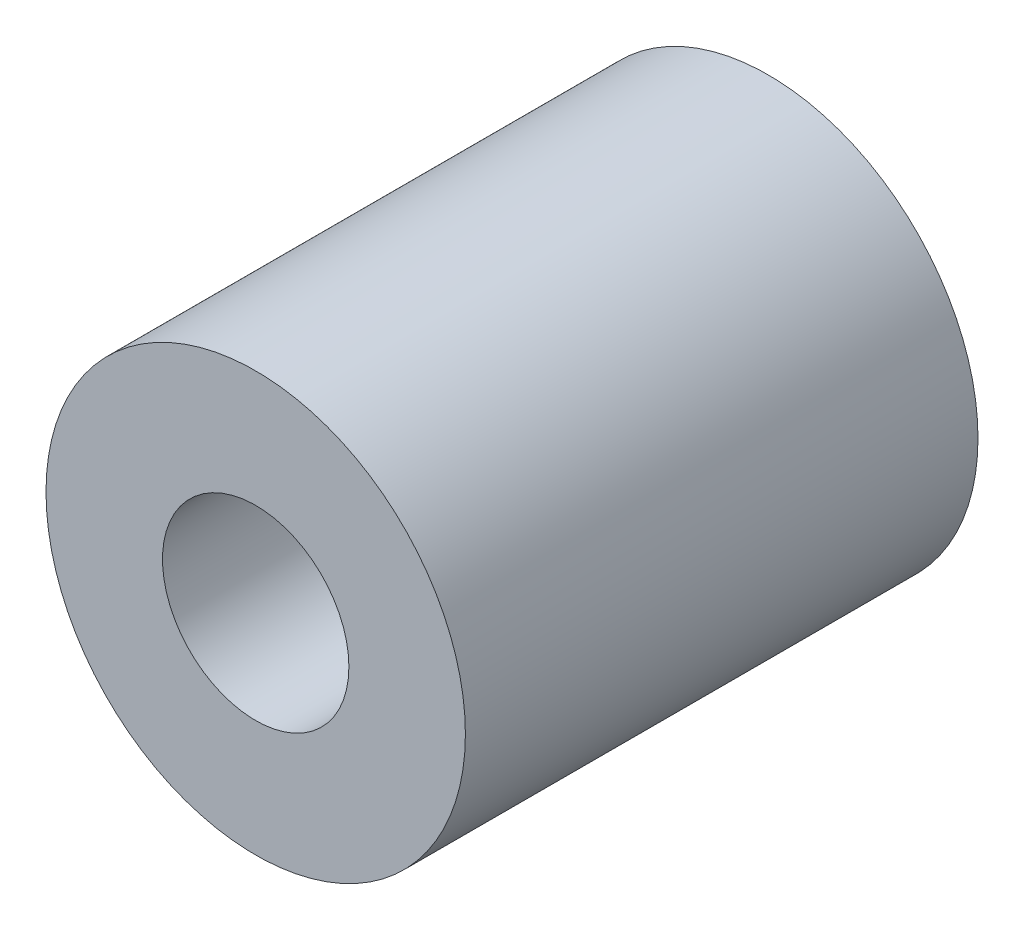
SolidWorks part; units mm, degrees
ref_plane "前视基准面" through (0, 0, 0) normal (0, 0, 1) x (1, 0, 0)
ref_plane "上视基准面" through (0, 0, 0) normal (0, 1, 0) x (1, 0, 0)
ref_plane "右视基准面" through (0, 0, 0) normal (1, 0, 0) x (0, 0, -1)
other "Configuration Table"
sketch "草图8" plane through (0, 0, 0) normal (0, 0, 1) x (1, 0, 0)
  circle A0 centre (0, 0) radius 45
  circle A1 centre (0, 0) radius 20
extrude "凸台-拉伸1" add sketch "草图8" along normal blind 110
